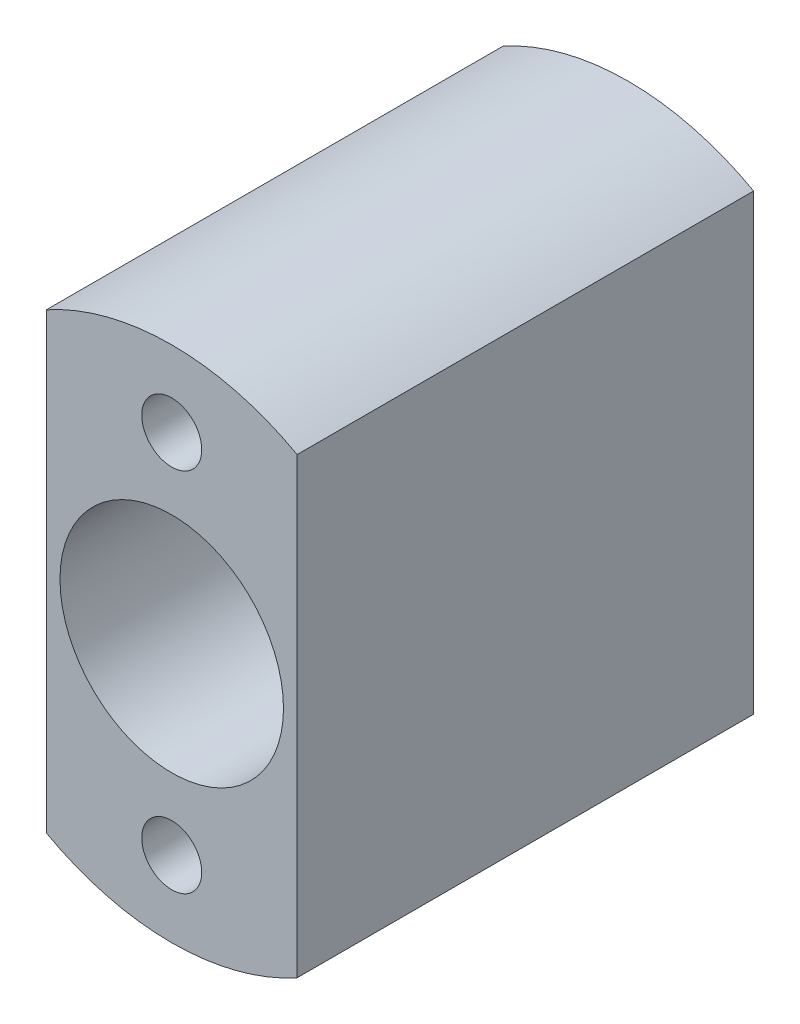
SolidWorks part; units mm, degrees
ref_plane "Front Plane" through (0, 0, 0) normal (0, 0, 1) x (1, 0, 0)
ref_plane "Top Plane" through (0, 0, 0) normal (0, 1, 0) x (1, 0, 0)
ref_plane "Right Plane" through (0, 0, 0) normal (1, 0, 0) x (0, 0, -1)
ref_plane "Plane1" through (0, 0, 9.5) normal (0, 0, 1) x (1, 0, 0)
sketch "Sketch1" plane through (0, 0, 0) normal (0, 0, 1) x (1, 0, 0)
  line L0 (0, 0) -> (0, 9.5) construction
  line L1 (-4.6, -8.312) -> (-4.6, 8.312)
  line L2 (4.6, -8.312) -> (4.6, 8.312)
  arc A0 (-4.6, -8.312) -> (4.6, -8.312) centre (0, 0) ccw
  arc A1 (4.6, 8.312) -> (-4.6, 8.312) centre (0, 0) ccw
  dimension "D1" = 19
  dimension "D2" = 9.2
extrude "Extrude1" add sketch "Sketch1" along normal blind 16.75
sketch "Sketch3" plane through (0, 0, 16.75) normal (0, 0, 1) x (1, 0, 0)
  line L0 (0, 0) -> (4.6, 0) construction
  line L1 (4.6, -8.312) -> (4.6, 8.312) construction
  circle A0 centre (0, 6.715) radius 1.1
  circle A1 centre (0, -6.715) radius 1.1
  dimension "D1" = 2.2
  dimension "D2" = 13.43
extrude "Cut-Extrude1" cut sketch "Sketch3" against normal through all
sketch "Sketch5" plane through (0, 0, 0) normal (0, 0, -1) x (-1, 0, 0)
  circle A0 centre (0, 0) radius 4.1
  dimension "D1" = 8.2
extrude "Cut-Extrude2" cut sketch "Sketch5" against normal blind 24
